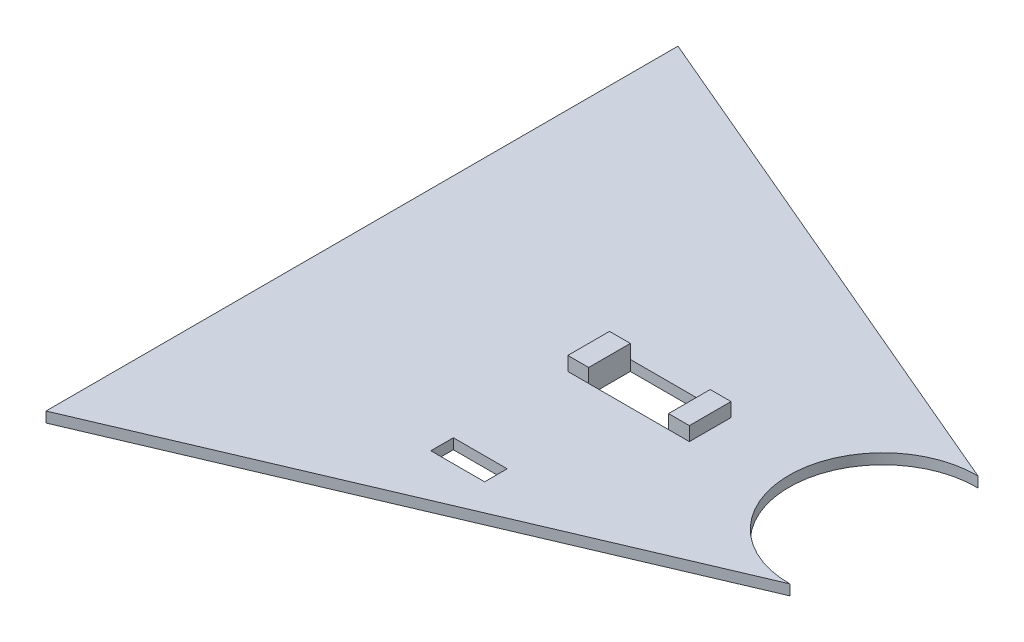
SolidWorks part; units mm, degrees
ref_plane "Front Plane" through (0, 0, 0) normal (0, 0, 1) x (1, 0, 0)
ref_plane "Top Plane" through (0, 0, 0) normal (0, 1, 0) x (1, 0, 0)
ref_plane "Right Plane" through (0, 0, 0) normal (1, 0, 0) x (0, 0, -1)
sketch "Sketch1" plane through (0, 0, 0) normal (0, 1, 0) x (1, 0, 0)
  line L1 (0, -91) -> (0, 91)
  line L2 (0, 91) -> (150.4052, 26.997)
  line L4 (0, -91) -> (150.2197, -26.9991)
  arc A2 (150.4052, 26.997) -> (150.2197, -26.9991) centre (150, 0) ccw
  dimension "D1" = 182
extrude "Boss-Extrude1" add sketch "Sketch1" along normal blind 3
sketch "Sketch2" plane through (0, 3, 0) normal (0, 1, 0) x (1, 0, 0)
  line L1 (65.323, -39.0076) -> (80.8238, -39.0076)
  line L2 (65.323, -39.0076) -> (65.323, -45.5076)
  line L3 (65.323, -45.5076) -> (80.8238, -45.5076)
  line L4 (80.8238, -39.0076) -> (80.8238, -45.5076)
  dimension "D1" = 15.5008
  dimension "D2" = 6.5
extrude "Cut-Extrude1" cut sketch "Sketch2" against normal through all
sketch "Sketch3" plane through (0, 3, 0) normal (0, 1, 0) x (1, 0, 0)
  line L0 (0, 0) -> (188.5611, 0) construction
  line L2 (71.2805, 6) -> (94.2805, 6)
  line L3 (71.2805, 6) -> (71.2805, -6)
  line L4 (71.2805, -6) -> (94.2805, -6)
  line L5 (94.2805, 6) -> (94.2805, -6)
  point P7 (94.2805, 0)
  dimension "D1" = 12
  dimension "D2" = 23
extrude "Cut-Extrude2" cut sketch "Sketch3" against normal through all contours L3 L2 L5 L4
sketch "Sketch4" plane through (0, 3, 0) normal (0, 1, 0) x (1, 0, 0)
  line L1 (94.2805, 6) -> (100.2805, 6)
  line L2 (94.2805, 6) -> (94.2805, -6)
  line L3 (94.2805, -6) -> (100.2805, -6)
  line L4 (100.2805, 6) -> (100.2805, -6)
  line L5 (71.2805, 6) -> (65.2805, 6)
  line L6 (71.2805, 6) -> (71.2805, -6)
  line L7 (71.2805, -6) -> (65.2805, -6)
  line L8 (65.2805, 6) -> (65.2805, -6)
  dimension "D1" = 6
  dimension "D2" = 6
extrude "Boss-Extrude2" add sketch "Sketch4" along normal blind 4 contours L6 L5 L8 L7 | L2 L1 L4 L3
equation "\"ed_\"= 182"
equation "\"rad_\"= 50 / 2"
equation "\"xdist_\"= 122"
equation "\"D1@Sketch1\"=\"ed_\""
